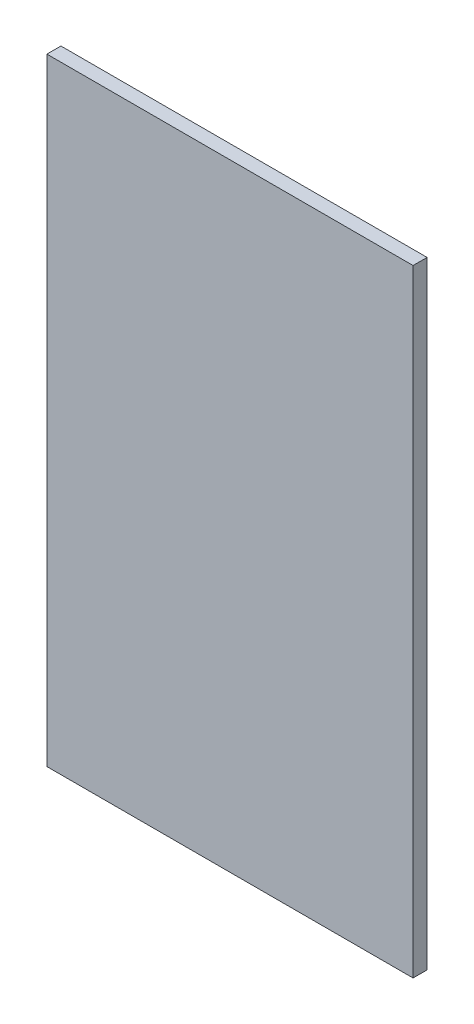
SolidWorks part; units mm, degrees
material "Teak"
ref_plane "Front Plane" through (0, 0, 0) normal (0, 0, 1) x (1, 0, 0)
ref_plane "Top Plane" through (0, 0, 0) normal (0, 1, 0) x (1, 0, 0)
ref_plane "Right Plane" through (0, 0, 0) normal (1, 0, 0) x (0, 0, -1)
sketch "Sketch1" plane through (0, 0, 0) normal (0, 0, 1) x (1, 0, 0)
  line L1 (0, 0) -> (470, 0)
  line L2 (0, 0) -> (0, 792)
  line L3 (0, 792) -> (470, 792)
  line L4 (470, 0) -> (470, 792)
  dimension "D1" = 470
  dimension "D2" = 792
extrude "Boss-Extrude1" add sketch "Sketch1" along normal blind 18
